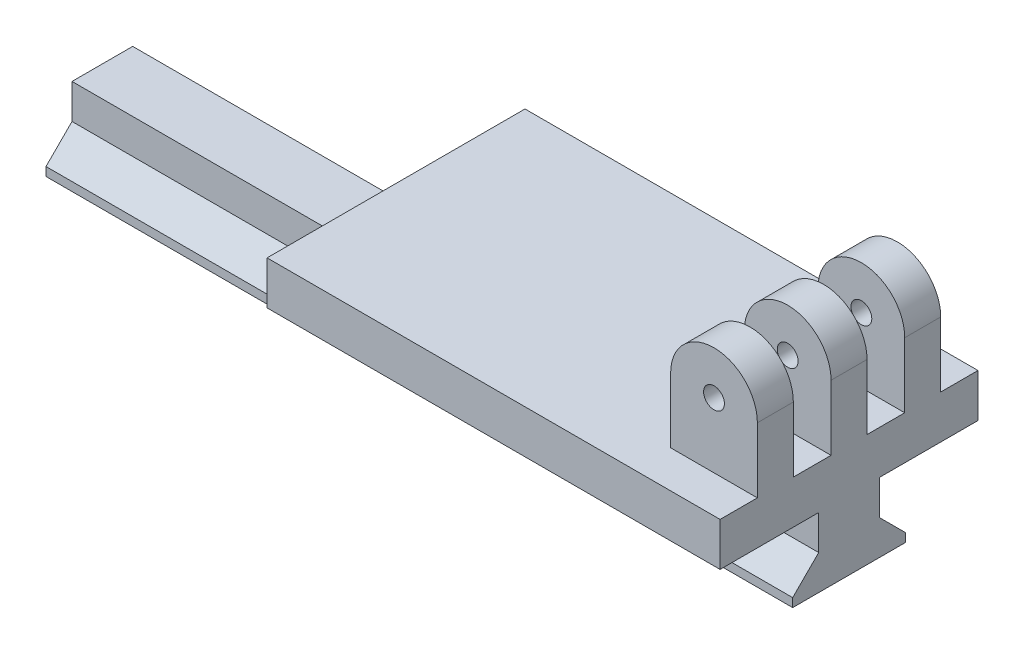
SolidWorks part; units mm, degrees
ref_plane "Front Plane" through (0, 0, 0) normal (0, 0, 1) x (1, 0, 0)
ref_plane "Top Plane" through (0, 0, 0) normal (0, 1, 0) x (1, 0, 0)
ref_plane "Right Plane" through (0, 0, 0) normal (1, 0, 0) x (0, 0, -1)
sketch "Sketch1" plane through (0, 0, 0) normal (0, 1, 0) x (1, 0, 0)
  line L1 (-52.25, 29.75) -> (52.25, 29.75)
  line L2 (-52.25, 29.75) -> (-52.25, -29.75)
  line L3 (-52.25, -29.75) -> (52.25, -29.75)
  line L4 (52.25, 29.75) -> (52.25, -29.75)
  line L5 (-52.25, 29.75) -> (52.25, -29.75) construction
  line L6 (-52.25, -29.75) -> (52.25, 29.75) construction
  point P0 (0, 0)
  dimension "D1" = 104.5
  dimension "D2" = 59.5
extrude "Boss-Extrude1" add sketch "Sketch1" along normal blind 10
sketch "Sketch3" plane through (0, 0, 0) normal (0, 0, 1) x (1, 0, 0)
  line L0 (52.25, 10) -> (52.25, 25)
  line L1 (52.25, 10) -> (32.25, 10)
  line L2 (-52.25, 10) -> (52.25, 10) construction
  line L3 (32.25, 10) -> (32.25, 25)
  arc A0 (32.25, 25) -> (52.25, 25) centre (42.25, 25) cw
  dimension "D1" = 15
  dimension "D2" = 20
extrude "Boss-Extrude2" add sketch "Sketch3" along normal up to surface and the other way up to surface up to face at (0, 5, 29.75) other way up to face at (0, 5, -29.75)
sketch "Sketch4" plane through (0, 10, 0) normal (0, 1, 0) x (1, 0, 0)
  line L6 (52.25, -29.75) -> (52.25, 29.75) construction
  line L16 (32.25, 29.75) -> (52.25, 29.75)
  line L17 (32.25, 29.75) -> (32.25, 21.15)
  line L18 (32.25, 21.15) -> (52.25, 21.15)
  line L20 (52.25, 29.75) -> (52.25, 21.15)
  line L21 (32.25, -29.75) -> (32.25, 29.75) construction
  line L22 (32.25, 12.85) -> (52.25, 12.85)
  line L23 (32.25, 12.85) -> (32.25, 4.15)
  line L24 (32.25, 4.15) -> (52.25, 4.15)
  line L25 (52.25, 12.85) -> (52.25, 4.15)
  line L26 (42.25, 21.15) -> (42.25, 12.85) construction
  line L27 (32.25, -4.15) -> (52.25, -4.15)
  line L28 (32.25, -4.15) -> (32.25, -12.85)
  line L29 (32.25, -12.85) -> (52.25, -12.85)
  line L30 (52.25, -4.15) -> (52.25, -12.85)
  line L31 (32.25, -21.15) -> (52.25, -21.15)
  line L32 (32.25, -21.15) -> (32.25, -29.75)
  line L33 (32.25, -29.75) -> (52.25, -29.75)
  line L34 (52.25, -21.15) -> (52.25, -29.75)
  line L35 (42.25, 4.15) -> (42.25, -4.15) construction
  line L36 (42.25, -12.85) -> (42.25, -21.15) construction
  dimension "D1" = 8.3
  dimension "D2" = 8.6
  dimension "D3" = 8.7
extrude "Cut-Extrude1" cut sketch "Sketch4" along normal through all
sketch "Sketch7" plane through (0, 0, 29.75) normal (0, 0, 1) x (1, 0, 0)
  circle A1 centre (42.25, 25) radius 10
  point P0 (42.25, 25)
hole_wizard "M4 Clearance Hole1" positions "Sketch7" profile "Sketch6" hole size "M4" standard "ANSI Metric" end condition through all
sketch "Sketch6" plane through (42.25, 25, 29.75) normal (1, 0, 0) x (0, -1, 0)
  line L0 (0, 0) -> (0, 59.5)
  line L1 (0, 59.5) -> (2.4, 59.5)
  line L2 (2.4, 59.5) -> (2.4, 0)
  line L5 (2.4, 0) -> (0, 0)
  line L11 (0, -6.35) -> (0, 107.95) construction
  dimension "Thru Hole Dia." = 4.8
  dimension "Thru Hole Depth" = 59.5
sketch "Sketch8" plane through (0, 0, 0) normal (1, 0, 0) x (0, 0, -1)
  line L0 (-7, 0) -> (-7, -8)
  line L1 (-29.75, 0) -> (29.75, 0) construction
  line L2 (-7, -8) -> (-13, -14)
  line L3 (-13, -14) -> (-13, -16)
  line L4 (-13, -16) -> (13, -16)
  line L5 (13, -16) -> (13, -14)
  line L6 (13, -14) -> (7, -8)
  line L7 (7, -8) -> (7, 0)
  line L8 (-7, 0) -> (7, 0)
  point P4 (0, 0)
  point P12 (0, 0)
  point P13 (0, 0)
  point P14 (0, -16)
  dimension "D1" = 14
  dimension "D2" = 8
  dimension "D3" = 6
  dimension "D4" = 2
  dimension "D5" = 6
extrude "Boss-Extrude3" add sketch "Sketch8" along normal up to surface and the other way blind 120 up to face at (52.25, 14.375, 0)
